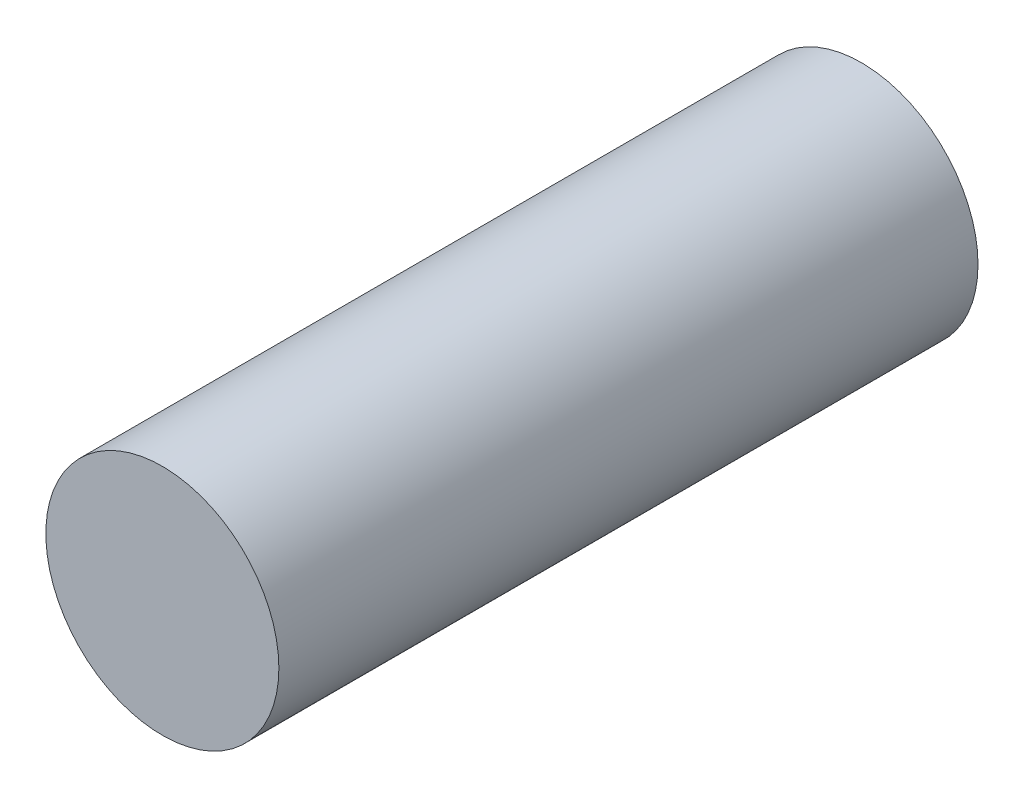
SolidWorks part; units mm, degrees
ref_plane "Front Plane" through (0, 0, 0) normal (0, 0, 1) x (1, 0, 0)
ref_plane "Top Plane" through (0, 0, 0) normal (0, 1, 0) x (1, 0, 0)
ref_plane "Right Plane" through (0, 0, 0) normal (1, 0, 0) x (0, 0, -1)
sketch "Sketch1" plane through (0, 0, 0) normal (0, 0, 1) x (1, 0, 0)
  circle A0 centre (0, 0) radius 10
  dimension "D1" = 20
extrude "Boss-Extrude1" add sketch "Sketch1" along normal blind 60
sketch "Sketch2" plane through (0, 0, 0) normal (0, 0, -1) x (-1, 0, 0)
  circle A0 centre (0, 0) radius 4
  dimension "D1" = 8
extrude "Cut-Extrude1" cut sketch "Sketch2" against normal blind 10
